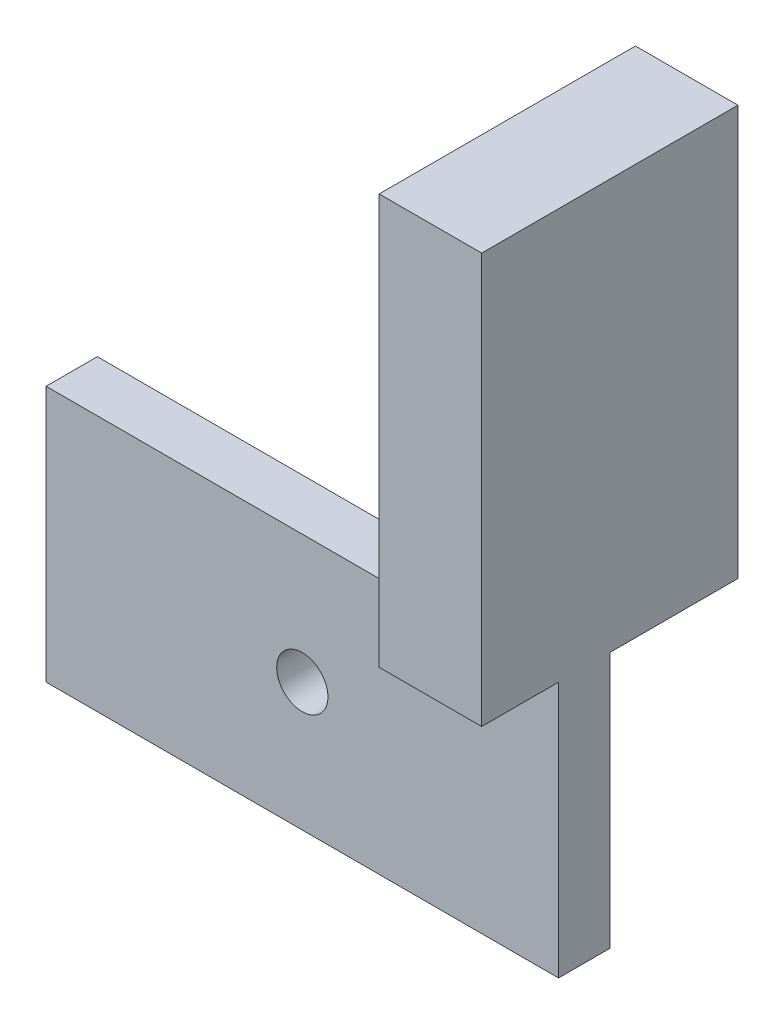
SolidWorks part; units mm, degrees
ref_plane "前视基准面" through (0, 0, 0) normal (0, 0, 1) x (1, 0, 0)
ref_plane "上视基准面" through (0, 0, 0) normal (0, 1, 0) x (1, 0, 0)
ref_plane "右视基准面" through (0, 0, 0) normal (1, 0, 0) x (0, 0, -1)
other "Configuration Table"
sketch "草图1" plane through (0, 0, 0) normal (0, 0, 1) x (1, 0, 0)
  line L1 (-500, -250) -> (500, -250)
  line L2 (-500, -250) -> (-500, 250)
  line L3 (-500, 250) -> (500, 250)
  line L4 (500, -250) -> (500, 250)
  line L5 (-500, -250) -> (500, 250) construction
  line L6 (-500, 250) -> (500, -250) construction
  point P0 (0, 0)
extrude "凸台-拉伸1" add sketch "草图1" along normal blind 100
sketch "草图2" plane through (0, 250, 0) normal (0, 1, 0) x (1, 0, 0)
  line L0 (500, 0) -> (-500, 0) construction
  line L1 (300, -250) -> (500, -250)
  line L2 (300, -250) -> (300, 250)
  line L3 (300, 250) -> (500, 250)
  line L4 (500, -250) -> (500, 250)
  line L5 (300, -250) -> (500, 250) construction
  line L6 (300, 250) -> (500, -250) construction
  point P0 (400, 0)
extrude "凸台-拉伸2" add sketch "草图2" along normal blind 800
sketch "草图3" plane through (0, 0, 0) normal (0, 0, 1) x (1, 0, 0)
  circle A0 centre (0, 0) radius 50
extrude "切除-拉伸1" cut sketch "草图3" along normal through all
